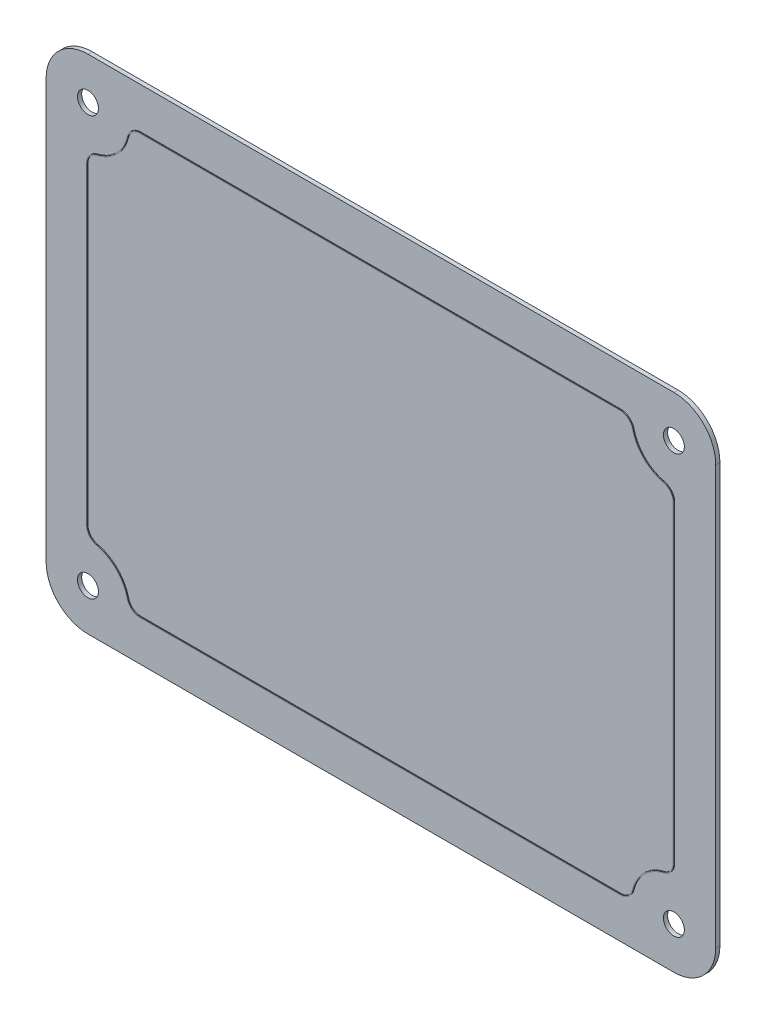
SolidWorks part; units mm, degrees
material "冷轧钢板"
ref_plane "前视基准面" through (0, 0, 0) normal (0, 0, 1) x (1, 0, 0)
ref_plane "上视基准面" through (0, 0, 0) normal (0, 1, 0) x (1, 0, 0)
ref_plane "右视基准面" through (0, 0, 0) normal (1, 0, 0) x (0, 0, -1)
sketch "草图1" plane through (0, 0, 0) normal (0, 0, 1) x (1, 0, 0)
  line L0 (0, 0) -> (123.6045, 0) construction
  line L1 (0, 0) -> (0, 118.0224) construction
  line L3 (-35, 30) -> (35, 30)
  line L4 (-40, 25) -> (-40, -25)
  line L5 (-35, -30) -> (35, -30)
  line L6 (40, 25) -> (40, -25)
  circle A0 centre (35, 25) radius 1.25
  arc A1 (-40, -25) -> (-35, -30) centre (-35, -25) ccw
  arc A2 (35, -30) -> (40, -25) centre (35, -25) ccw
  arc A3 (-35, 30) -> (-40, 25) centre (-35, 25) ccw
  arc A4 (35, 30) -> (40, 25) centre (35, 25) cw
  circle A5 centre (-35, 25) radius 1.25
  circle A6 centre (-35, -25) radius 1.25
  circle A7 centre (35, -25) radius 1.25
  point P12 (-40, -30)
  point P15 (40, -30)
  point P20 (40, 30)
  dimension "D5" = 2.5
  dimension "D8" = 5
  dimension "D9" = 2.5
  dimension "D10" = 2.5
  dimension "D11" = 2.5
  dimension "D1" = 60
  dimension "D2" = 30
  dimension "D3" = 80
  dimension "D4" = 40
  dimension "D6" = 35
  dimension "D7" = 25
extrude "凸台-拉伸1" add sketch "草图1" along normal blind 0.5
sketch "草图4" plane through (0, 0, 0.5) normal (0, 0, 1) x (1, 0, 0)
  line L0 (0, 0) -> (48.5109, 0) construction
  line L1 (0, 0) -> (0, 40.8727) construction
  line L2 (-28.6754, 25.1) -> (28.6754, 25.1)
  line L3 (-28.6754, 25) -> (28.6754, 25)
  line L4 (-35, 18.6754) -> (-35, -18.6754)
  line L5 (-28.6754, -25) -> (28.6754, -25)
  line L6 (35, 18.6754) -> (35, -18.6754)
  line L7 (-35, 25) -> (35, -25) construction
  line L8 (-35, -25) -> (35, 25) construction
  line L9 (35.1, 18.6754) -> (35.1, -18.6754)
  line L10 (-28.6754, -25.1) -> (28.6754, -25.1)
  line L11 (-35.1, 18.6754) -> (-35.1, -18.6754)
  arc A0 (-33.8462, 20.135) -> (-30.135, 23.8462) centre (-35, 25) ccw
  arc A1 (-35, 18.6754) -> (-33.8462, 20.135) centre (-33.5, 18.6754) cw
  arc A2 (-30.135, 23.8462) -> (-28.6754, 25) centre (-28.6754, 23.5) cw
  arc A3 (35, 18.6754) -> (33.8462, 20.135) centre (33.5, 18.6754) ccw
  arc A4 (33.8462, 20.135) -> (30.135, 23.8462) centre (35, 25) cw
  arc A5 (30.135, 23.8462) -> (28.6754, 25) centre (28.6754, 23.5) ccw
  arc A6 (35, -18.6754) -> (33.8462, -20.135) centre (33.5, -18.6754) cw
  arc A7 (33.8462, -20.135) -> (30.135, -23.8462) centre (35, -25) ccw
  arc A8 (30.135, -23.8462) -> (28.6754, -25) centre (28.6754, -23.5) cw
  arc A9 (-30.135, -23.8462) -> (-28.6754, -25) centre (-28.6754, -23.5) ccw
  arc A10 (-33.8462, -20.135) -> (-30.135, -23.8462) centre (-35, -25) cw
  arc A11 (-35, -18.6754) -> (-33.8462, -20.135) centre (-33.5, -18.6754) ccw
  arc A12 (30.2323, 23.8692) -> (28.6754, 25.1) centre (28.6754, 23.5) ccw
  arc A13 (33.8692, 20.2323) -> (30.2323, 23.8692) centre (35, 25) cw
  arc A14 (35.1, 18.6754) -> (33.8692, 20.2323) centre (33.5, 18.6754) ccw
  arc A15 (35.1, -18.6754) -> (33.8692, -20.2323) centre (33.5, -18.6754) cw
  arc A16 (33.8692, -20.2323) -> (30.2323, -23.8692) centre (35, -25) ccw
  arc A17 (30.2323, -23.8692) -> (28.6754, -25.1) centre (28.6754, -23.5) cw
  arc A18 (-30.2323, -23.8692) -> (-28.6754, -25.1) centre (-28.6754, -23.5) ccw
  arc A19 (-33.8692, -20.2323) -> (-30.2323, -23.8692) centre (-35, -25) cw
  arc A20 (-35.1, -18.6754) -> (-33.8692, -20.2323) centre (-33.5, -18.6754) ccw
  arc A21 (-35.1, 18.6754) -> (-33.8692, 20.2323) centre (-33.5, 18.6754) cw
  arc A22 (-33.8692, 20.2323) -> (-30.2323, 23.8692) centre (-35, 25) ccw
  arc A23 (-30.2323, 23.8692) -> (-28.6754, 25.1) centre (-28.6754, 23.5) cw
  dimension "D3" = 10
  dimension "D5" = 1.5
  dimension "D6" = 1.5
  dimension "D1" = 70
  dimension "D2" = 50
  dimension "D4" = 0.1
extrude "凸台-拉伸5" add sketch "草图4" along normal blind 0.1
